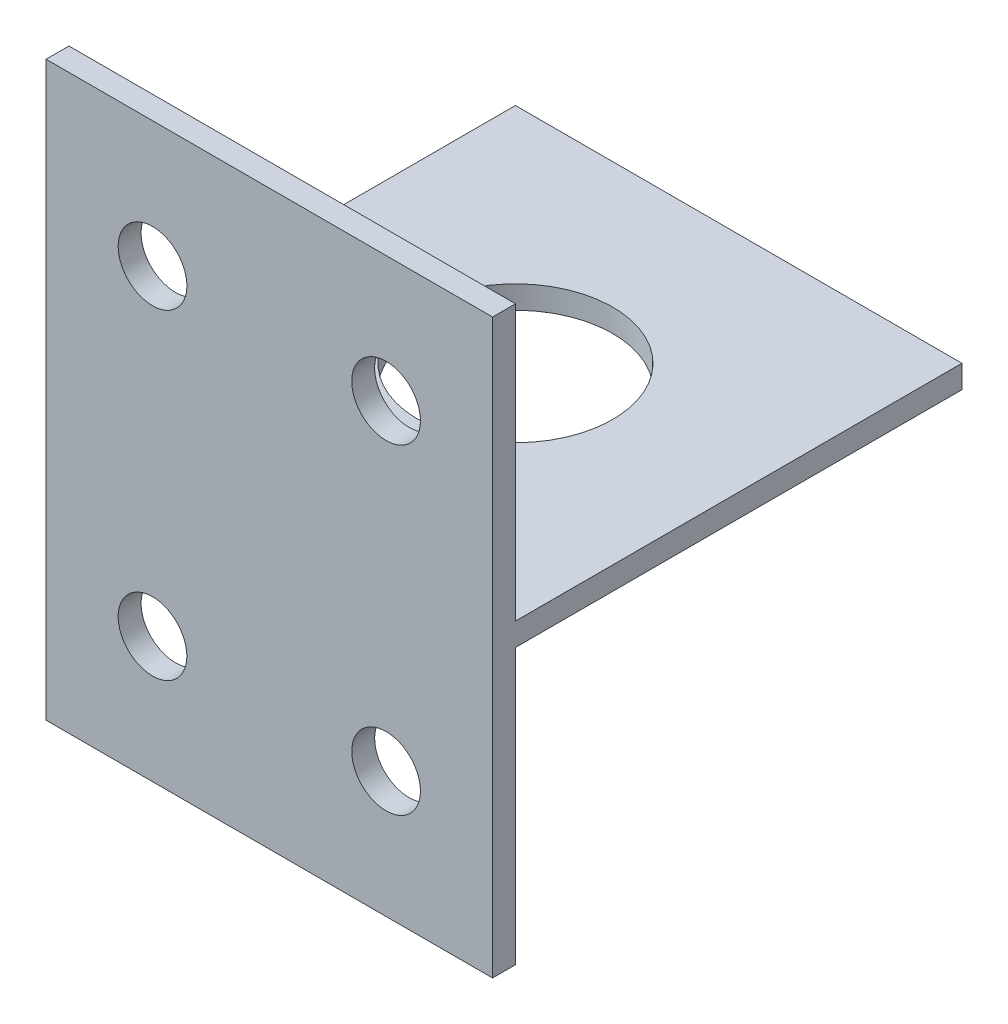
SolidWorks part; units mm, degrees
ref_plane "前视基准面" through (0, 0, 0) normal (0, 0, 1) x (1, 0, 0)
ref_plane "上视基准面" through (0, 0, 0) normal (0, 1, 0) x (1, 0, 0)
ref_plane "右视基准面" through (0, 0, 0) normal (1, 0, 0) x (0, 0, -1)
sketch "草图1" plane through (0, 0, 0) normal (0, 0, 1) x (1, 0, 0)
  line L1 (9.75, -12.5) -> (-9.75, -12.5)
  line L2 (9.75, -12.5) -> (9.75, 12.5)
  line L3 (9.75, 12.5) -> (-9.75, 12.5)
  line L4 (-9.75, -12.5) -> (-9.75, 12.5)
  line L5 (9.75, -12.5) -> (-9.75, 12.5) construction
  line L6 (9.75, 12.5) -> (-9.75, -12.5) construction
  point P0 (0, 0)
  dimension "D1" = 25
  dimension "D2" = 19.5
extrude "凸台-拉伸1" add sketch "草图1" along normal blind 1
sketch "草图2" plane through (0, 0, 0) normal (0, 0, -1) x (-1, 0, 0)
  line L0 (9.75, -12.5) -> (-9.75, -12.5) construction
  line L1 (9.75, -0.5) -> (-9.75, -0.5)
  line L2 (9.75, -0.5) -> (9.75, 0.5)
  line L3 (9.75, 0.5) -> (-9.75, 0.5)
  line L4 (-9.75, -0.5) -> (-9.75, 0.5)
  line L5 (9.75, -0.5) -> (-9.75, 0.5) construction
  line L6 (9.75, 0.5) -> (-9.75, -0.5) construction
  point P0 (0, 0)
  dimension "D1" = 1
extrude "凸台-拉伸2" add sketch "草图2" along normal blind 19.5
sketch "草图3" plane through (0, 0, 0) normal (0, 0, -1) x (-1, 0, 0)
  line L0 (0, 12.5) -> (0, 7.0023) construction
  line L1 (-9.75, 12.5) -> (9.75, 12.5) construction
  line L2 (0, 7.0023) -> (5.1006, 7.0023) construction
  line L3 (10.725, 0) -> (-10.725, 0) construction
  circle A0 centre (5.1006, 7.0023) radius 1.5
  circle A1 centre (-5.1006, 7.0023) radius 1.5
  circle A2 centre (5.1006, -7.0023) radius 1.5
  circle A3 centre (-5.1006, -7.0023) radius 1.5
  dimension "D1" = 3
extrude "切除-拉伸1" cut sketch "草图3" against normal through all
sketch "草图4" plane through (0, 0.5, 0) normal (0, 1, 0) x (1, 0, 0)
  line L0 (-9.75, 19.5) -> (9.75, 0) construction
  circle A0 centre (0, 9.75) radius 4.25
  dimension "D1" = 8.5
extrude "切除-拉伸2" cut sketch "草图4" against normal through all
